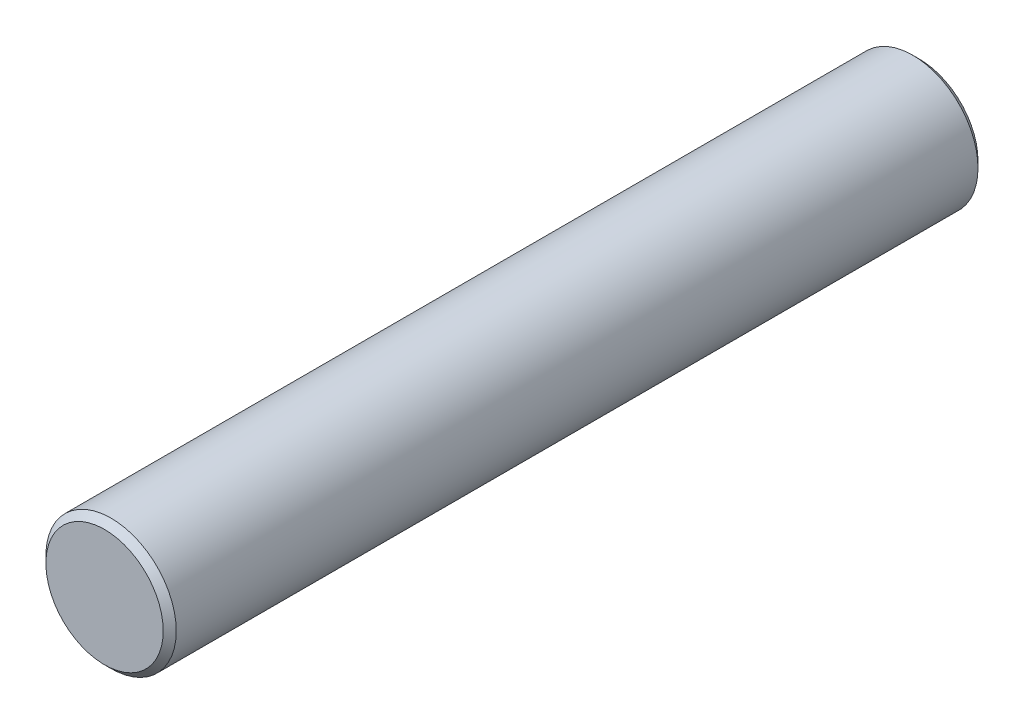
SolidWorks part; units mm, degrees
ref_plane "Спереди" through (0, 0, 0) normal (0, 0, 1) x (1, 0, 0)
ref_plane "Сверху" through (0, 0, 0) normal (0, 1, 0) x (1, 0, 0)
ref_plane "Справа" through (0, 0, 0) normal (1, 0, 0) x (0, 0, -1)
sketch "Эскиз1" plane through (0, 0, 0) normal (0, 0, 1) x (1, 0, 0)
  circle A0 centre (0, 0) radius 10
  dimension "D1" = 20
extrude "Бобышка-Вытянуть1" add sketch "Эскиз1" along normal blind 125
chamfer "Фаска1" distance 1 angle 45 2 edges at (10, 0, 125) (10, 0, 0)
